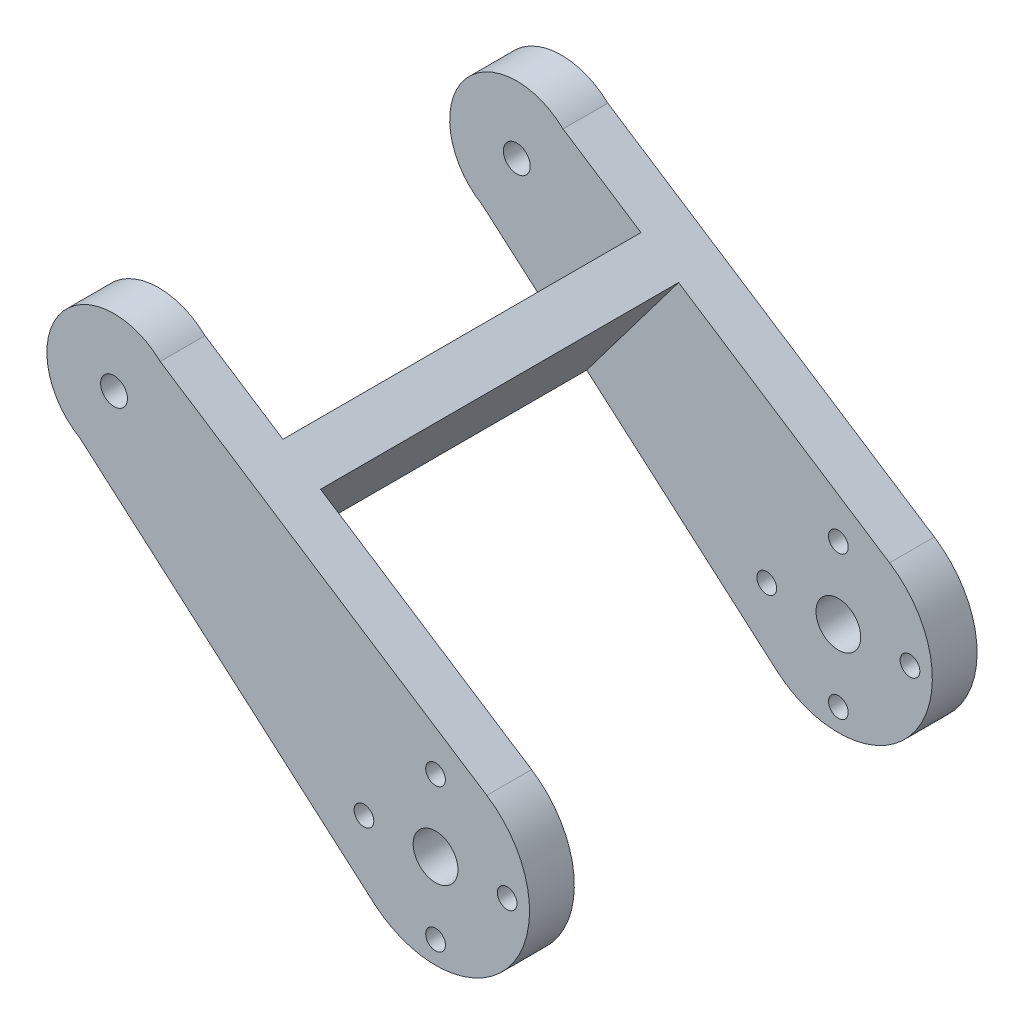
SolidWorks part; units mm, degrees
ref_plane "Plan de face" through (0, 0, 0) normal (0, 0, 1) x (1, 0, 0)
ref_plane "Plan de dessus" through (0, 0, 0) normal (0, 1, 0) x (1, 0, 0)
ref_plane "Plan de droite" through (0, 0, 0) normal (1, 0, 0) x (0, 0, -1)
sketch "Esquisse1" plane through (0, 0, 0) normal (0, 0, 1) x (1, 0, 0)
  line L0 (0, 0) -> (0, 13.0667) construction
  line L1 (5.7264, 8.8011) -> (-30.7551, 32.5377)
  line L2 (0, 0) -> (-35.923, 27.1023) construction
  line L3 (-6.8908, -7.9225) -> (-39.7308, 20.6408)
  circle A0 centre (0, 8) radius 1.1
  circle A1 centre (8, 0) radius 1.1
  circle A2 centre (0, -8) radius 1.1
  circle A3 centre (-8, 0) radius 1.1
  arc A4 (-6.8908, -7.9225) -> (5.7264, 8.8011) centre (0, 0) ccw
  arc A5 (-30.7551, 32.5377) -> (-39.7308, 20.6408) centre (-35.923, 27.1023) ccw
  circle A6 centre (-35.923, 27.1023) radius 1.5
  circle A7 centre (0, 0) radius 2.5
  point P14 (0, 0)
  dimension "D1" = 8
  dimension "D3" = 45
  dimension "D2" = 4
extrude "Boss.-Extru.1" add sketch "Esquisse1" along normal blind 5
sketch "Esquisse2" plane through (0, 0, 0) normal (0, 0, -1) x (-1, 0, 0)
  line L0 (35.923, 27.1023) -> (0, 0) construction
  line L1 (17.8479, 24.1396) -> (28.1119, 10.535)
  line L2 (-5.7264, 8.8011) -> (30.7551, 32.5377) construction
  line L5 (39.7308, 20.6408) -> (6.8908, -7.9225) construction
  line L6 (22.049, 26.873) -> (31.8937, 13.8243)
  line L7 (17.8479, 24.1396) -> (22.049, 26.873)
  line L8 (31.8937, 13.8243) -> (28.1119, 10.535)
  dimension "D3" = 90
extrude "Boss.-Extru.2" add sketch "Esquisse2" along normal blind 20
mirror "Symétrie1" about plane through (0, 0, -20) normal (0, 0, 1) of "Boss.-Extru.1", "Boss.-Extru.2"
